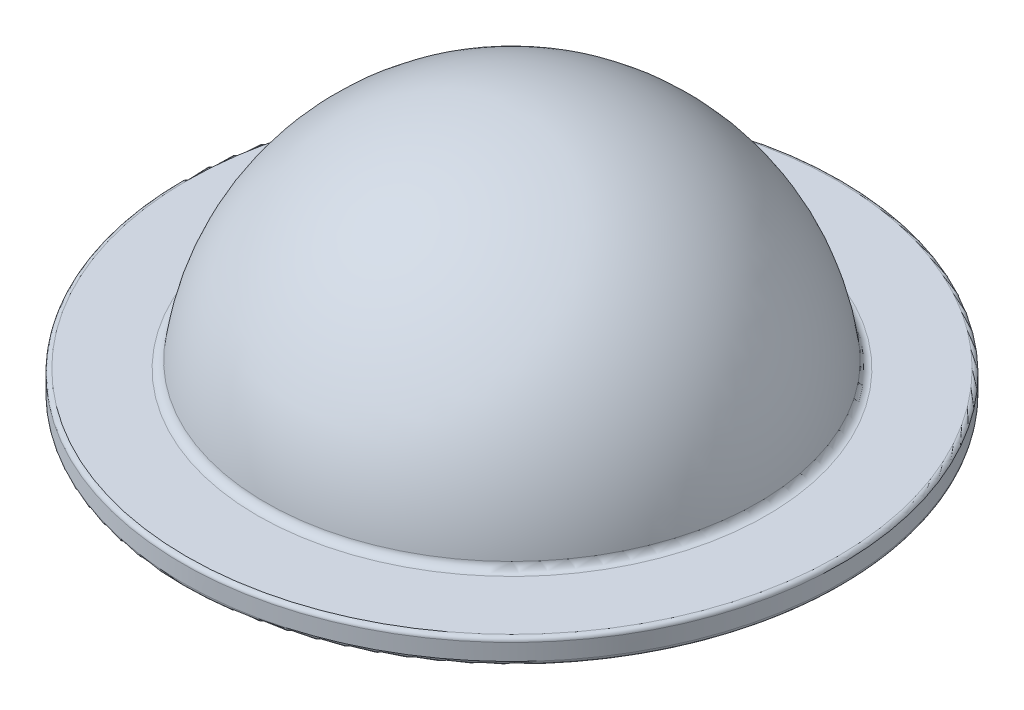
SolidWorks part; units mm, degrees
ref_plane "Front Plane" through (0, 0, 0) normal (0, 0, 1) x (1, 0, 0)
ref_plane "Top Plane" through (0, 0, 0) normal (0, 1, 0) x (1, 0, 0)
ref_plane "Right Plane" through (0, 0, 0) normal (1, 0, 0) x (0, 0, -1)
sketch "草图1" plane through (0, 0, 0) normal (0, 0, 1) x (1, 0, 0)
  line L1 (-27.1496, 0) -> (27.1496, 0) construction
  line L3 (-27.1496, 0) -> (-40, 0)
  line L5 (27.1496, 0) -> (40, 0) construction
  line L6 (30, 3) -> (40, 3) construction
  line L7 (-30, 3) -> (-40, 3)
  line L8 (-40, 3) -> (-40, 0)
  line L10 (40, 3) -> (40, 0) construction
  line L12 (0, 27.1496) -> (0, 30.1496)
  arc A0 (-27.1496, 0) -> (27.1496, 0) centre (0, 0) cw construction
  arc A1 (-30, 3) -> (30, 3) centre (0, 0) cw construction
  arc A2 (-27.1496, 0) -> (0, 27.1496) centre (0, 0) cw
  arc A3 (-30, 3) -> (0, 30.1496) centre (0, 0) cw
  dimension "D1" = 3
  dimension "D2" = 60
  dimension "D3" = 10
revolve "旋转4" add sketch "草图1" angle 360 about L12
fillet "圆角1" radius 1 1 edges at (0, 3, -30)
fillet "圆角2" radius 3 1 edges at (0, 0, -27.1496)
fillet "圆角3" radius 0.5 2 edges at (0, 3, -40) (0, 0, -40)
